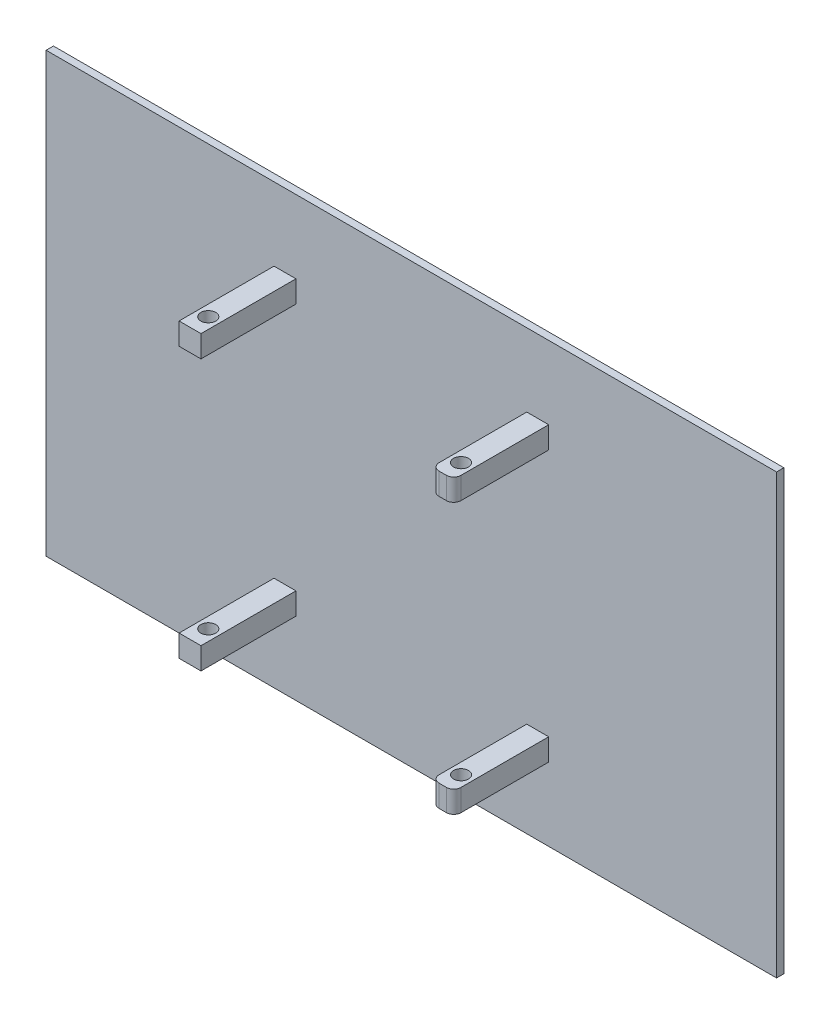
SolidWorks part; units mm, degrees
ref_plane "Plano frontal" through (0, 0, 0) normal (0, 0, 1) x (1, 0, 0)
ref_plane "Plano superior" through (0, 0, 0) normal (0, 1, 0) x (1, 0, 0)
ref_plane "Plano direito" through (0, 0, 0) normal (1, 0, 0) x (0, 0, -1)
sketch "Esboço1" plane through (0, 0, 0) normal (0, 0, 1) x (1, 0, 0)
  line L1 (-50, -30) -> (50, -30)
  line L2 (-50, -30) -> (-50, 30)
  line L3 (-50, 30) -> (50, 30)
  line L4 (50, -30) -> (50, 30)
  line L5 (-50, -30) -> (50, 30) construction
  line L6 (-50, 30) -> (50, -30) construction
  point P0 (0, 0)
extrude "Ressalto-extrusão1" add sketch "Esboço1" along normal blind 1
sketch "Esboço2" plane through (0, 0, 0) normal (0, 0, 1) x (1, 0, 0)
  line L0 (-50, 0) -> (50, 0) construction
  line L1 (15.8, 17) -> (18.8, 17)
  line L2 (15.8, 17) -> (15.8, 20)
  line L3 (15.8, 20) -> (18.8, 20)
  line L4 (18.8, 17) -> (18.8, 20)
  line L5 (15.8, 17) -> (18.8, 20) construction
  line L6 (15.8, 20) -> (18.8, 17) construction
  line L7 (-50, 30) -> (-50, -30) construction
  line L8 (50, -30) -> (50, 30) construction
  line L9 (0, -30) -> (0, 30) construction
  line L10 (15.8, -20) -> (18.8, -20)
  line L11 (15.8, -17) -> (18.8, -17)
  line L12 (15.8, -17) -> (15.8, -20)
  line L13 (18.8, -17) -> (18.8, -20)
  line L14 (-50, -30) -> (50, -30) construction
  line L15 (50, 30) -> (-50, 30) construction
  line L16 (-15.8, -17) -> (-15.8, -20)
  line L17 (-15.8, -20) -> (-18.8, -20)
  line L18 (-18.8, -17) -> (-18.8, -20)
  line L19 (-15.8, -17) -> (-18.8, -17)
  line L20 (-18.8, 17) -> (-18.8, 20)
  line L21 (-15.8, 20) -> (-18.8, 20)
  line L22 (-15.8, 17) -> (-15.8, 20)
  line L23 (-15.8, 17) -> (-18.8, 17)
  point P0 (17.3, 18.5)
  dimension "D1" = 34
  dimension "D2" = 3
  dimension "D3" = 3
  dimension "D4" = 17.3
extrude "Ressalto-extrusão2" add sketch "Esboço2" along normal blind 14
ref_plane "Plano1" through (0, -20, 0) normal (0, -1, 0) x (-1, 0, 0)
sketch "Esboço3" plane through (0, -20, 0) normal (0, -1, 0) x (-1, 0, 0)
  line L0 (-15.8, -1) -> (-18.8, -1) construction
  line L3 (-18.8, -14) -> (-18.8, -1) construction
  circle A0 centre (-17.3, -11.5) radius 1.025
  circle A1 centre (17.3, -11.5) radius 1.025
  dimension "D1" = 10.5
  dimension "D2" = 1.5
extrude "Corte-extrusão1" cut sketch "Esboço3" against normal through all both and the other way through all contours A0 | A1
fillet "Filete1" radius 1 1 edges at (15.8, -18.5, 14)
fillet "Filete2" radius 1 3 edges at (15.8, 18.5, 14) (18.8, 18.5, 14) (18.8, -18.5, 14)
